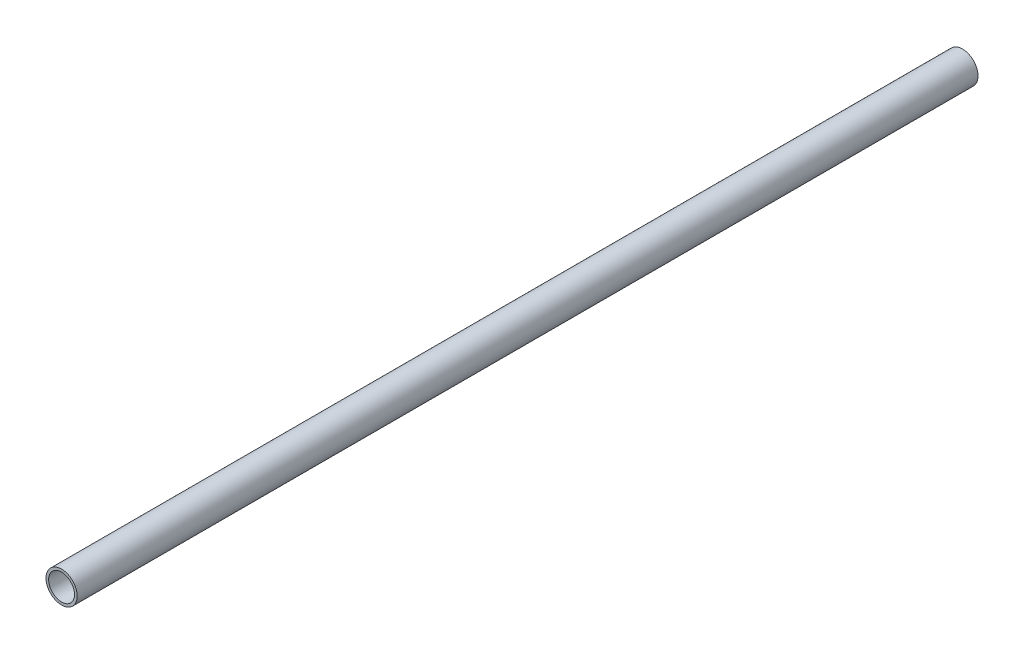
SolidWorks part; units mm, degrees
material "Plain Carbon Steel"
ref_plane "Front Plane" through (0, 0, 0) normal (0, 0, 1) x (1, 0, 0)
ref_plane "Top Plane" through (0, 0, 0) normal (0, 1, 0) x (1, 0, 0)
ref_plane "Right Plane" through (0, 0, 0) normal (1, 0, 0) x (0, 0, -1)
sketch "Sketch1" plane through (0, 0, 0) normal (0, 0, 1) x (1, 0, 0)
  circle A0 centre (0, 0) radius 21.082
  circle A1 centre (0, 0) radius 17.526
  dimension "D1" = 42.164
  dimension "D2" = 3.556
extrude "Boss-Extrude1" add sketch "Sketch1" along normal blind 1219.2
